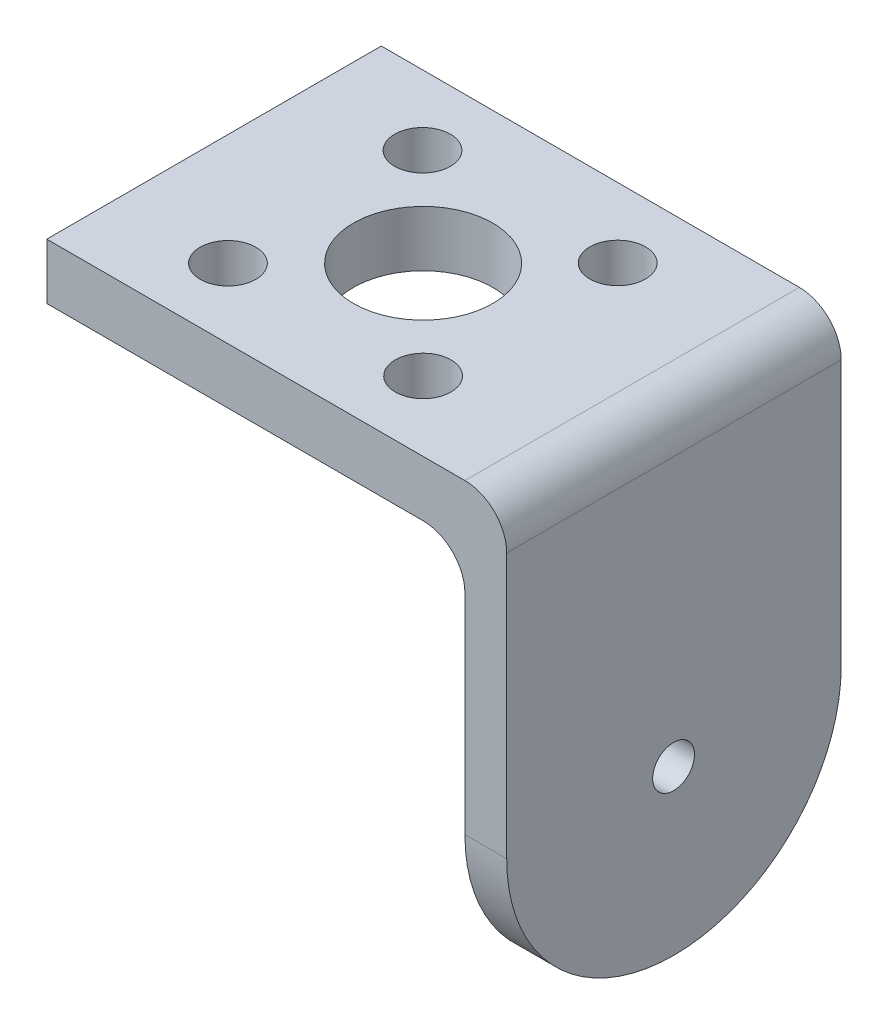
SolidWorks part; units mm, degrees
ref_plane "前视基准面" through (0, 0, 0) normal (0, 0, 1) x (1, 0, 0)
ref_plane "上视基准面" through (0, 0, 0) normal (0, 1, 0) x (1, 0, 0)
ref_plane "右视基准面" through (0, 0, 0) normal (1, 0, 0) x (0, 0, -1)
sketch "草图1" plane through (0, 0, 0) normal (0, 0, 1) x (1, 0, 0)
  line L0 (30, -7) -> (30, -34)
  line L2 (0, 0) -> (0, -4)
  line L3 (0, -4) -> (27, -4)
  line L6 (32.9975, -3) -> (32.9975, -34)
  line L7 (30, -34) -> (32.9975, -34)
  line L8 (0, 0) -> (29.9975, 0)
  arc A0 (27, -4) -> (30, -7) centre (27, -7) cw
  arc A1 (32.9975, -3) -> (29.9975, 0) centre (29.9975, -3) ccw
extrude "凸台-拉伸1" add sketch "草图1" along normal blind 24
sketch "草图4" plane through (32.9975, 0, 0) normal (1, 0, 0) x (0, 0, -1)
  line L3 (0, -22) -> (0, -34)
  line L4 (-24, -22) -> (-24, -34)
  line L5 (-24, -34) -> (0, -34)
  line L6 (-12, -22) -> (-12, -34)
  arc A0 (-24, -22) -> (0, -22) centre (-12, -22) ccw
  line M4 (-24, -3) -> (-24, -34)
  line M5 (-24, -34) -> (0, -34)
extrude "切除-拉伸2" cut sketch "草图4" against normal blind 40 and the other way through all contours A0 M4 M5
sketch "草图7" plane through (32.9975, 0, 0) normal (1, 0, 0) x (0, 0, -1)
  line L0 (0, -22) -> (3.396, -22)
  line L1 (0, -22) -> (0, -34)
  line L2 (-12, -34) -> (0, -34)
  arc A0 (-12, -34) -> (0, -22) centre (-12, -22) ccw
  line M2 (-12, -34) -> (0, -34)
  line M3 (0, -34) -> (0, -3)
extrude "切除-拉伸3" cut sketch "草图7" against normal blind 40 contours A0 M2 M3
sketch "草图8" plane through (0, 0, 0) normal (0, 1, 0) x (1, 0, 0)
  circle A0 centre (15, -12) radius 5
  circle A1 centre (8, -19) radius 2
  circle A2 centre (22, -19) radius 2
  circle A3 centre (7.9576, -5.0001) radius 2
  circle A4 centre (21.9576, -5.0001) radius 2
  dimension "D1" = 2
  dimension "D2" = 2
  dimension "D3" = 2
extrude "切除-拉伸4" cut sketch "草图8" against normal blind 40 contours A3 | A2 | A4 | A0 | A1
sketch "草图9" plane through (32.9975, 0, 0) normal (1, 0, 0) x (0, 0, -1)
  circle A0 centre (-12.0279, -22.2557) radius 1.5
extrude "切除-拉伸5" cut sketch "草图9" against normal blind 10
sketch "草图10" plane through (0, -4, 0) normal (0, -1, 0) x (-1, 0, 0)
  line L0 (-7.9576, -5.0001) -> (-8, -19) construction
  line L1 (-8, -19) -> (-22, -19) construction
  line L2 (-22, -19) -> (-21.9576, -5.0001) construction
  line L3 (-21.9576, -5.0001) -> (-7.9576, -5.0001) construction
  line L4 (0, -24) -> (0, 0) construction
  circle A0 centre (-7.9576, -5.0001) radius 2 construction
  dimension "D1" = 13.9999
  dimension "D2" = 14
